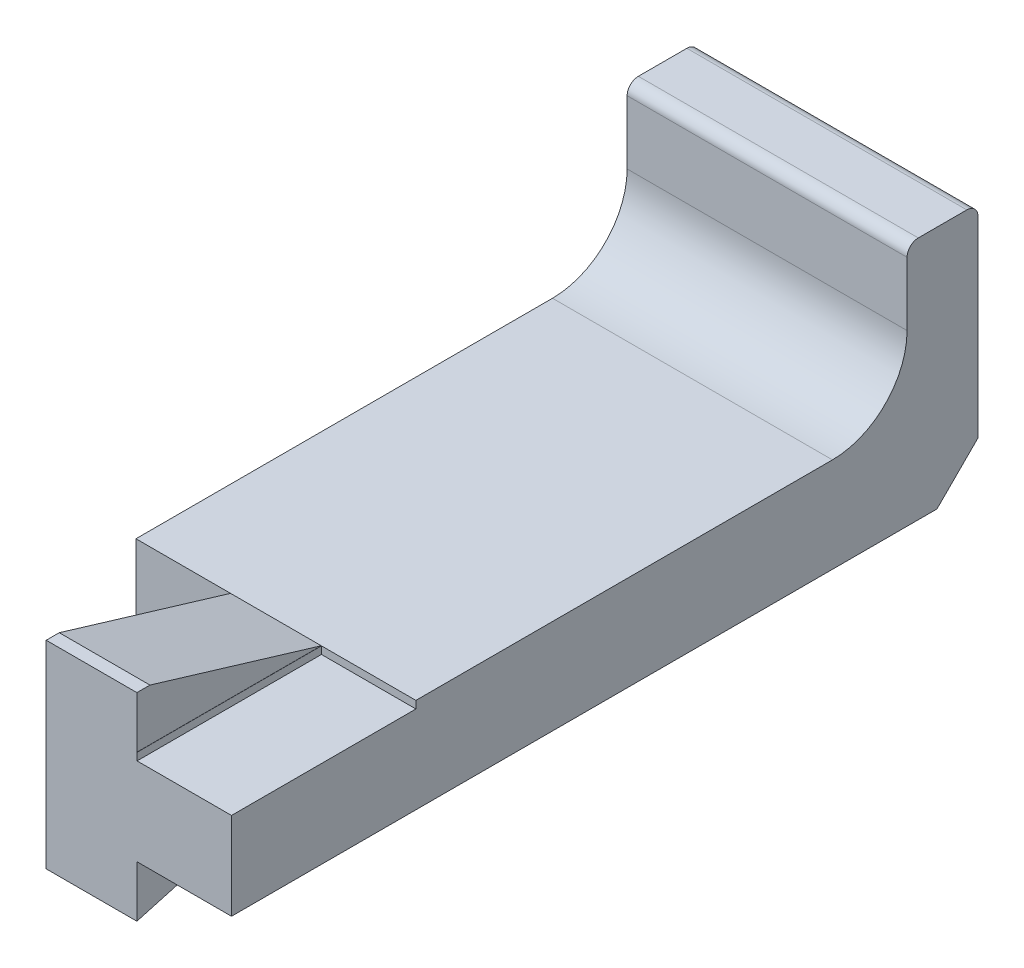
SolidWorks part; units mm, degrees
ref_plane "Front Plane" through (0, 0, 0) normal (0, 0, 1) x (1, 0, 0)
ref_plane "Top Plane" through (0, 0, 0) normal (0, 1, 0) x (1, 0, 0)
ref_plane "Right Plane" through (0, 0, 0) normal (1, 0, 0) x (0, 0, -1)
sketch "Sketch1" plane through (0, 0, 0) normal (0, 1, 0) x (1, 0, 0)
  line L1 (-9.525, -25.4) -> (9.525, -25.4)
  line L2 (-9.525, -25.4) -> (-9.525, 25.4)
  line L3 (-9.525, 25.4) -> (9.525, 25.4)
  line L4 (9.525, -25.4) -> (9.525, 25.4)
  line L5 (-9.525, -25.4) -> (9.525, 25.4) construction
  line L6 (-9.525, 25.4) -> (9.525, -25.4) construction
  line L11 (-9.525, -25.4) -> (-3.0988, -25.4)
  line L12 (-9.525, -25.4) -> (-9.525, -12.8524)
  line L13 (-9.525, -12.8524) -> (-3.0988, -12.8524)
  line L14 (-3.0988, -25.4) -> (-3.0988, -12.8524)
  point P0 (0, 0)
  dimension "D1" = 50.8
  dimension "D2" = 19.05
  dimension "D3" = 12.5476
  dimension "D4" = 6.4262
extrude "Boss-Extrude1" add sketch "Sketch1" along normal blind 6.4516 contours L14 L1 L4 L3 L2 L13
sketch "Sketch2" plane through (0, 6.4516, 0) normal (0, 1, 0) x (1, 0, 0)
  line L0 (9.525, -25.4) -> (9.525, 25.4) construction
  line L1 (-9.525, 25.4) -> (9.525, 25.4)
  line L2 (-9.525, 25.4) -> (-9.525, 20.574)
  line L3 (-9.525, 20.574) -> (9.525, 20.574)
  line L4 (9.525, 25.4) -> (9.525, 20.574)
  point P14 (0, 0)
  dimension "D1" = 4.826
extrude "Boss-Extrude2" add sketch "Sketch2" along normal blind 10.16
fillet "Fillet1" radius 5.08 1 edges at (0, 6.4516, -20.574)
fillet "Fillet2" radius 0.762 2 edges at (0, 16.6116, -20.574) (0, 16.6116, -25.4)
sketch "Sketch4" plane through (0, 6.4516, 0) normal (0, 1, 0) x (1, 0, 0)
  line L0 (-9.525, -12.8524) -> (-3.0988, -12.8524) construction
  line L1 (9.525, -25.4) -> (3.0988, -25.4)
  line L2 (9.525, -25.4) -> (9.525, -12.8524)
  line L3 (9.525, -12.8524) -> (3.0988, -12.8524)
  line L4 (3.0988, -25.4) -> (3.0988, -12.8524)
  dimension "D1" = 6.4262
extrude "Cut-Extrude1" cut sketch "Sketch4" against normal blind 0.508
sketch "Sketch5" plane through (0, 0, 0) normal (1, 0, 0) x (0, 0, -1)
  line L0 (-25.4, 6.4516) -> (-12.8524, 6.4516)
  line L1 (-12.8524, 6.4516) -> (-24.511, 9.9632)
  line L2 (-24.511, 9.9632) -> (-25.4, 9.9632)
  line L3 (-25.4, 9.9632) -> (-25.4, 6.4516)
  line L4 (-25.4, 0) -> (-25.4, -3.5116)
  line L5 (10.4775, 0) -> (-10.4775, 0) construction
  line L6 (-25.4, 5.9436) -> (-25.4, 0) construction
  line L7 (-25.4, -3.5116) -> (-12.8524, 0)
  line L8 (-12.8524, 0) -> (-25.4, 0)
  dimension "D1" = 3.5116
  dimension "D2" = 0.889
  dimension "D3" = 3.5116
extrude "Boss-Extrude3" add sketch "Sketch5" along normal mid plane 6.1722
chamfer "Chamfer1" distance 2.794 angle 45 1 edges at (0, 0, -25.4)
sketch "Sketch6" plane through (0, 0, 0) normal (0, -1, 0) x (1, 0, 0)
  line L0 (3.175, 23.8517) -> (7.239, 23.8517)
  line L1 (7.239, 23.8517) -> (7.239, -21.9964)
  line L2 (7.239, -21.9964) -> (-7.239, -21.9964)
  line L3 (-7.239, -21.9964) -> (-7.239, 10.703)
  line L4 (-7.239, 10.703) -> (-3.175, 10.703)
  line L5 (-3.175, 10.703) -> (-3.175, 1.2731)
  line L6 (-3.175, 1.2731) -> (3.175, 1.2731)
  line L7 (3.175, 1.2731) -> (3.175, 23.8517)
  line L8 (9.525, 25.4) -> (9.525, -22.606) construction
  line L10 (-9.525, 12.8524) -> (-9.525, -22.606) construction
  line L11 (9.525, -25.4) -> (-9.525, -25.4) construction
  point P10 (0, 0)
  point P11 (0, 0)
  point P12 (0, 0)
  dimension "D1" = 2.286
  dimension "D2" = 4.064
  dimension "D3" = 2.286
  dimension "D4" = 3.4036
  dimension "D5" = 4.064
extrude "Cut-Extrude2" cut sketch "Sketch6" against normal blind 3.556
